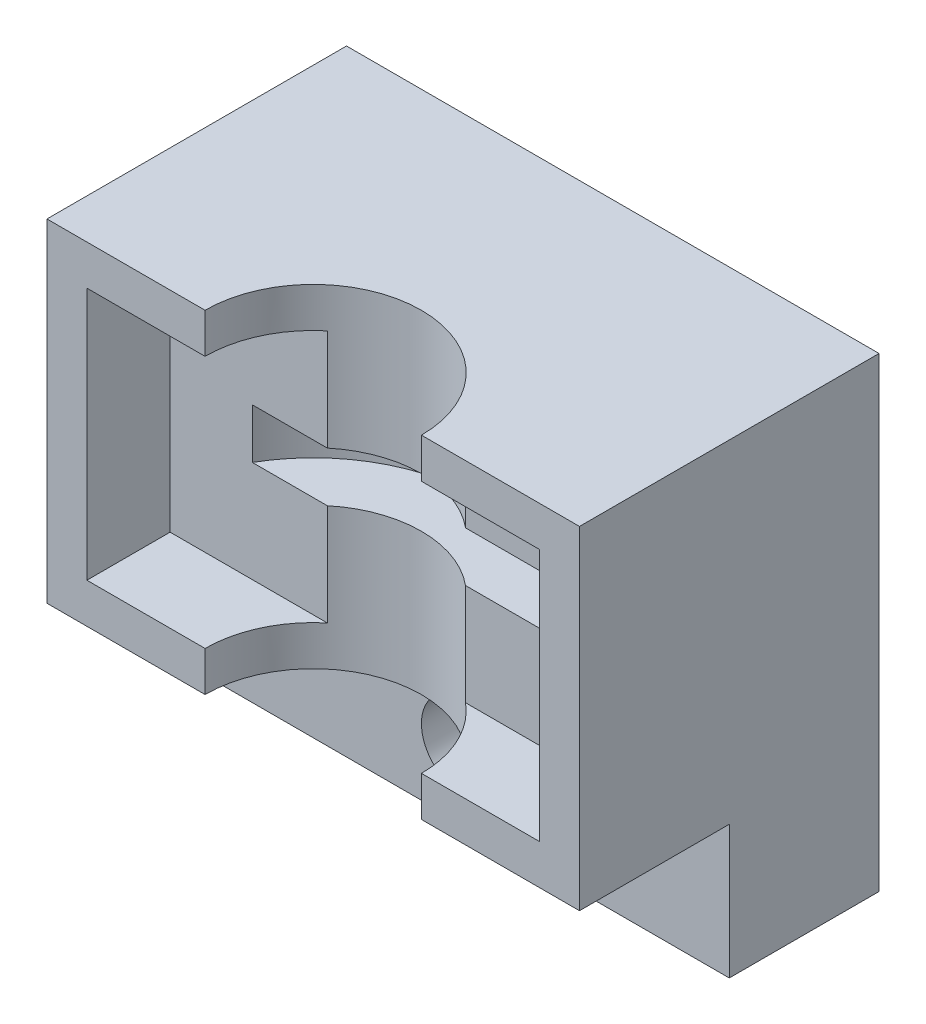
SolidWorks part; units mm, degrees
ref_plane "Спереди" through (0, 0, 0) normal (0, 0, 1) x (1, 0, 0)
ref_plane "Сверху" through (0, 0, 0) normal (0, 1, 0) x (1, 0, 0)
ref_plane "Справа" through (0, 0, 0) normal (1, 0, 0) x (0, 0, -1)
sketch "Эскиз1" plane through (0, 0, 0) normal (0, 0, 1) x (1, 0, 0)
  line L1 (-80, -70) -> (80, -70)
  line L2 (-80, -70) -> (-80, 70)
  line L3 (-80, 70) -> (80, 70)
  line L4 (80, -70) -> (80, 70)
  line L5 (-80, -70) -> (80, 70) construction
  line L6 (-80, 70) -> (80, -70) construction
  point P0 (0, 0)
  dimension "D1" = 160
  dimension "D2" = 140
extrude "Бобышка-Вытянуть1" add sketch "Эскиз1" along normal blind 45
sketch "Эскиз2" plane through (0, 0, 45) normal (0, 0, 1) x (1, 0, 0)
  line L0 (80, -70) -> (80, 70) construction
  line L1 (-80, 70) -> (80, 70)
  line L2 (-80, 70) -> (-80, -30)
  line L3 (-80, -30) -> (80, -30)
  line L4 (80, 70) -> (80, -30)
  dimension "D1" = 100
extrude "Бобышка-Вытянуть2" add sketch "Эскиз2" along normal blind 45
sketch "Эскиз3" plane through (0, 0, 45) normal (0, 0, 1) x (1, 0, 0)
  line L0 (80, -50) -> (-80, -50) construction
  line L1 (80, -70) -> (80, -30) construction
  line L2 (-80, -30) -> (-80, -70) construction
  circle A0 centre (0, -50) radius 12.5
  dimension "D1" = 25
extrude "Вырез-Вытянуть1" cut sketch "Эскиз3" against normal through all
sketch "Эскиз4" plane through (0, -30, 0) normal (0, -1, 0) x (1, 0, 0)
  line L0 (-80, 90) -> (80, 90) construction
  circle A0 centre (0, 90) radius 32.5
  dimension "D1" = 65
extrude "Вырез-Вытянуть2" cut sketch "Эскиз4" against normal through all
ref_plane "Плоскость1" through (0, 20, 0) normal (0, -1, 0) x (-1, 0, 0)
sketch "Эскиз5" plane through (0, 20, 0) normal (0, -1, 0) x (-1, 0, 0)
  circle A0 centre (0, -90) radius 50
  dimension "D1" = 100
extrude "Вырез-Вытянуть3" cut sketch "Эскиз5" against normal mid plane 15
sketch "Эскиз7" plane through (0, 0, 90) normal (0, 0, 1) x (1, 0, 0)
  line L0 (-80, 20) -> (80, 20) construction
  line L1 (-80, 70) -> (-80, -30) construction
  line L2 (80, -30) -> (80, 70) construction
  line L3 (-32.5, 70) -> (-80, 70) construction
  line L4 (68, 58) -> (-68, 58)
  line L5 (68, 58) -> (68, -18)
  line L6 (68, -18) -> (-68, -18)
  line L7 (-68, 58) -> (-68, -18)
  line L8 (68, 58) -> (-68, -18) construction
  line L9 (68, -18) -> (-68, 58) construction
  point P6 (0, 20)
  dimension "D1" = 12
  dimension "D2" = 12
extrude "Вырез-Вытянуть4" cut sketch "Эскиз7" against normal blind 25
